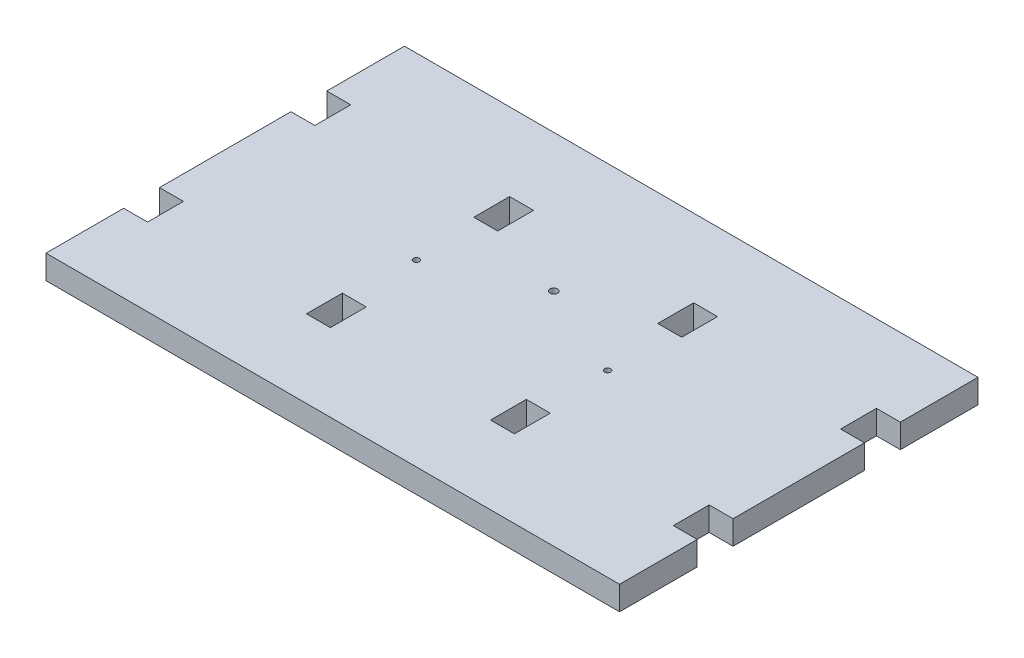
SolidWorks part; units mm, degrees
material "Acrylic (Medium-high impact)"
ref_plane "Front Plane" through (0, 0, 0) normal (0, 0, 1) x (1, 0, 0)
ref_plane "Top Plane" through (0, 0, 0) normal (0, 1, 0) x (1, 0, 0)
ref_plane "Right Plane" through (0, 0, 0) normal (1, 0, 0) x (0, 0, -1)
sketch "Sketch1" plane through (0, 0, 0) normal (0, 1, 0) x (1, 0, 0)
  line L1 (-152.4, 95.25) -> (152.4, 95.25)
  line L2 (-152.4, 95.25) -> (-152.4, -95.25)
  line L3 (-152.4, -95.25) -> (152.4, -95.25)
  line L4 (152.4, 95.25) -> (152.4, -95.25)
  line L5 (-152.4, 95.25) -> (152.4, -95.25) construction
  line L6 (-152.4, -95.25) -> (152.4, 95.25) construction
  point P0 (0, 0)
extrude "Extrude1" add sketch "Sketch1" along normal blind 12.7
sketch "Sketch2" plane through (0, 12.7, 0) normal (0, 1, 0) x (1, 0, 0)
  line L0 (0, 0) -> (0, 93.8784) construction
  line L1 (0, 0) -> (156.2405, 0) construction
  line L2 (-55.245, 53.975) -> (-55.245, 34.925)
  line L3 (42.545, 53.975) -> (55.245, 53.975)
  line L4 (42.545, 53.975) -> (42.545, 34.925)
  line L5 (42.545, 34.925) -> (55.245, 34.925)
  line L6 (55.245, 53.975) -> (55.245, 34.925)
  line L7 (-42.545, 34.925) -> (-55.245, 34.925)
  line L8 (-42.545, 53.975) -> (-42.545, 34.925)
  line L9 (-42.545, 53.975) -> (-55.245, 53.975)
  line L10 (-42.545, -53.975) -> (-55.245, -53.975)
  line L11 (-42.545, -53.975) -> (-42.545, -34.925)
  line L12 (-42.545, -34.925) -> (-55.245, -34.925)
  line L13 (55.245, -53.975) -> (55.245, -34.925)
  line L14 (42.545, -34.925) -> (55.245, -34.925)
  line L15 (42.545, -53.975) -> (42.545, -34.925)
  line L16 (42.545, -53.975) -> (55.245, -53.975)
  line L17 (-55.245, -53.975) -> (-55.245, -34.925)
  line L18 (152.4, -95.25) -> (152.4, 95.25) construction
  line L19 (152.4, 53.975) -> (139.7, 53.975)
  line L20 (152.4, 53.975) -> (152.4, 34.925)
  line L21 (152.4, 34.925) -> (139.7, 34.925)
  line L22 (139.7, 53.975) -> (139.7, 34.925)
  line L23 (-139.7, 53.975) -> (-139.7, 34.925)
  line L24 (-152.4, 34.925) -> (-139.7, 34.925)
  line L25 (-152.4, 53.975) -> (-152.4, 34.925)
  line L26 (-152.4, 53.975) -> (-139.7, 53.975)
  line L27 (139.7, -53.975) -> (139.7, -34.925)
  line L28 (152.4, -34.925) -> (139.7, -34.925)
  line L29 (152.4, -53.975) -> (152.4, -34.925)
  line L30 (152.4, -53.975) -> (139.7, -53.975)
  line L31 (-152.4, -53.975) -> (-139.7, -53.975)
  line L32 (-152.4, -53.975) -> (-152.4, -34.925)
  line L33 (-152.4, -34.925) -> (-139.7, -34.925)
  line L34 (-139.7, -53.975) -> (-139.7, -34.925)
  dimension "D1" = 19.05
  dimension "D2" = 12.7
  dimension "D3" = 42.545
  dimension "D4" = 34.925
extrude "Extrude2" cut sketch "Sketch2" against normal through all
sketch "Sketch3" plane through (0, 0, 0) normal (0, -1, 0) x (1, 0, 0)
  circle A0 centre (50.8, 0) radius 1.5875
  circle A1 centre (-50.8, 0) radius 1.5875
  dimension "D1" = 3.175
extrude "Cut-Extrude1" cut sketch "Sketch3" against normal through all
sketch "Sketch4" plane through (0, 12.7, 0) normal (0, 1, 0) x (1, 0, 0)
  circle A0 centre (0, 22.225) radius 2.032 construction
  circle A1 centre (0, 22.225) radius 2.032
extrude "Cut-Extrude2" cut sketch "Sketch4" against normal through all
